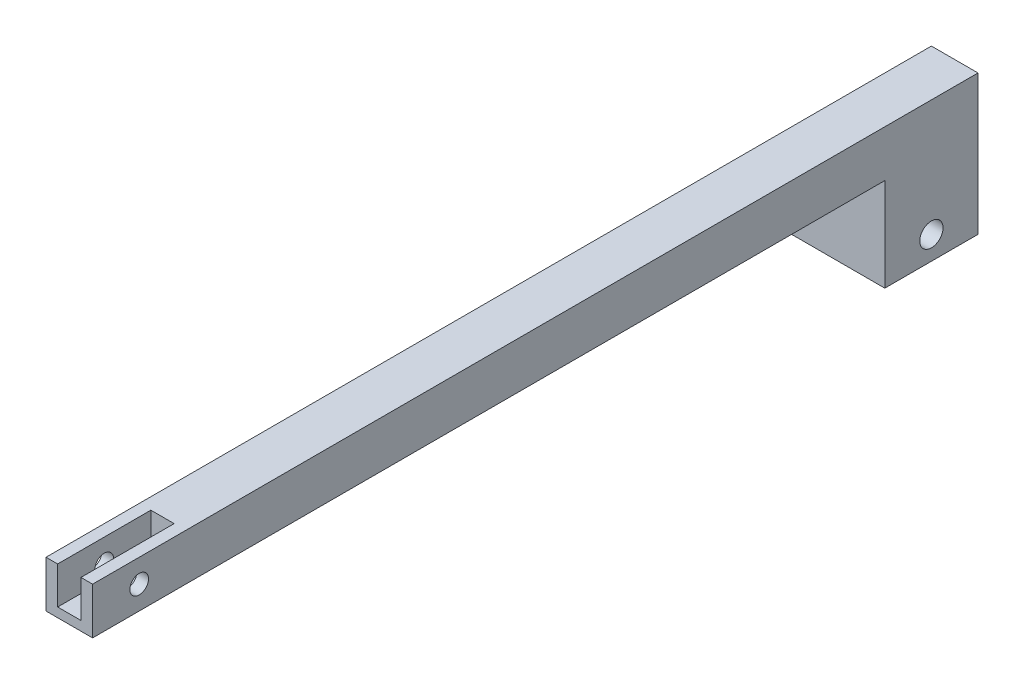
SolidWorks part; units mm, degrees
ref_plane "Front Plane" through (0, 0, 0) normal (0, 0, 1) x (1, 0, 0)
ref_plane "Top Plane" through (0, 0, 0) normal (0, 1, 0) x (1, 0, 0)
ref_plane "Right Plane" through (0, 0, 0) normal (1, 0, 0) x (0, 0, -1)
sketch "Sketch2" plane through (0, 0, 0) normal (0, 0, 1) x (1, 0, 0)
  line L0 (0, 0) -> (0, 10)
  line L1 (0, 10) -> (10, 10)
  line L2 (10, 10) -> (10, 30)
  line L3 (10, 30) -> (20, 30)
  line L4 (20, 30) -> (20, 0)
  line L5 (20, 0) -> (0, 0)
  dimension "D1" = 10
  dimension "D2" = 10
  dimension "D3" = 30
  dimension "D4" = 20
extrude "Boss-Extrude1" add sketch "Sketch2" along normal blind 190
sketch "Sketch3" plane through (0, 0, 0) normal (0, -1, 0) x (1, 0, 0)
  line L0 (20, 190) -> (20, 0) construction
  line L1 (20, 20) -> (10, 20)
  line L2 (20, 20) -> (20, 190)
  line L3 (20, 190) -> (10, 190)
  line L4 (10, 20) -> (10, 190)
  line L5 (0, 190) -> (20, 190) construction
  line L6 (0, 0) -> (20, 0) construction
  line L7 (0, 190) -> (0, 0) construction
  dimension "D1" = 20
  dimension "D2" = 10
extrude "Cut-Extrude2" cut sketch "Sketch3" against normal blind 20
sketch "Sketch4" plane through (10, 0, 0) normal (1, 0, 0) x (0, 0, -1)
  line L1 (-190, 10) -> (-20, 10)
  line L2 (-190, 10) -> (-190, 0)
  line L3 (-190, 0) -> (-20, 0)
  line L4 (-20, 10) -> (-20, 0)
extrude "Cut-Extrude3" cut sketch "Sketch4" against normal blind 20
sketch "Sketch5" plane through (0, 0, 0) normal (-1, 0, 0) x (0, 0, 1)
  line L0 (20, 0) -> (20, 10) construction
  line L1 (20, 0) -> (0, 0) construction
  circle A0 centre (10, 5) radius 2.75
  dimension "D1" = 5.5
  dimension "D2" = 10
  dimension "D3" = 5
extrude "Cut-Extrude4" cut sketch "Sketch5" against normal blind 10
sketch "Sketch6" plane through (0, 30, 0) normal (0, 1, 0) x (1, 0, 0)
  line L0 (20, -190) -> (10, -190) construction
  line L1 (12.5, -170) -> (17.5, -170)
  line L2 (12.5, -170) -> (12.5, -190)
  line L3 (12.5, -190) -> (17.5, -190)
  line L4 (17.5, -170) -> (17.5, -190)
  line L5 (10, -190) -> (10, 0) construction
  line L6 (20, -190) -> (20, 0) construction
  dimension "D1" = 2.5
  dimension "D2" = 20
  dimension "D3" = 2.5
extrude "Cut-Extrude5" cut sketch "Sketch6" against normal blind 5
ref_plane "Plane1" through (0, 10, 20) normal (0, 1, 0) x (1, 0, 0)
sketch "Sketch9" plane through (0, 0, 0) normal (-1, 0, 0) x (0, 0, 1)
  circle A0 centre (10, 5) radius 2.5
  circle A1 centre (10, 5) radius 2.75
  dimension "D1" = 5.5
  dimension "D2" = 5
extrude "Boss-Extrude2" add sketch "Sketch9" against normal through all
sketch "Sketch10" plane through (0, 0, 0) normal (-1, 0, 0) x (0, 0, 1)
  circle A0 centre (10, 5) radius 2.5
extrude "Cut-Extrude6" cut sketch "Sketch10" against normal through all
sketch "Sketch11" plane through (0, 25, 0) normal (0, 1, 0) x (1, 0, 0)
  line L1 (12.5, -170) -> (17.5, -170)
  line L2 (12.5, -170) -> (12.5, -190)
  line L3 (12.5, -190) -> (17.5, -190)
  line L4 (17.5, -170) -> (17.5, -190)
extrude "Cut-Extrude7" cut sketch "Sketch11" against normal blind 3
sketch "Sketch12" plane through (10, 0, 0) normal (-1, 0, 0) x (0, 0, 1)
  line L0 (190, 30) -> (0, 30) construction
  line L1 (190, 30) -> (190, 20) construction
  circle A0 centre (180, 25) radius 2
  dimension "D1" = 4
  dimension "D2" = 5
  dimension "D3" = 10
extrude "Cut-Extrude8" cut sketch "Sketch12" against normal through all
